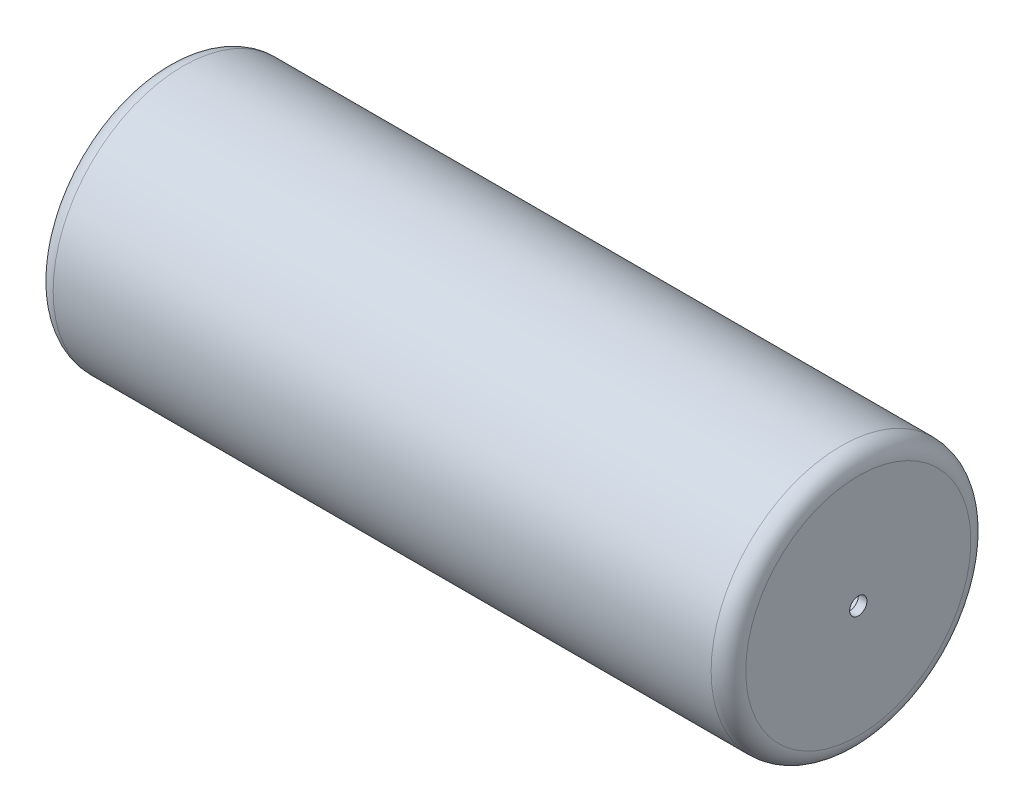
SolidWorks part; units mm, degrees
ref_plane "Front Plane" through (0, 0, 0) normal (0, 0, 1) x (1, 0, 0)
ref_plane "Top Plane" through (0, 0, 0) normal (0, 1, 0) x (1, 0, 0)
ref_plane "Right Plane" through (0, 0, 0) normal (1, 0, 0) x (0, 0, -1)
sketch "Sketch1" plane through (0, 0, 0) normal (0, 0, 1) x (1, 0, 0)
  line L0 (0, 0) -> (80, 0)
  line L1 (80, 0) -> (80, 15)
  line L2 (80, 15) -> (0, 15)
  line L3 (0, 15) -> (0, 0)
  dimension "D1" = 80
  dimension "D2" = 15
revolve "Revolve1" add sketch "Sketch1" angle 360 about L0
sketch "Sketch2" plane through (80, 0, 0) normal (1, 0, 0) x (0, 0, -1)
  circle A0 centre (0, 0) radius 1
  dimension "D1" = 2
shell "Shell2" thickness 1
extrude "Cut-Extrude1" cut sketch "Sketch2" against normal blind 10
fillet "Fillet1" radius 2 2 edges at (0, 0, 15) (80, 0, 15)
